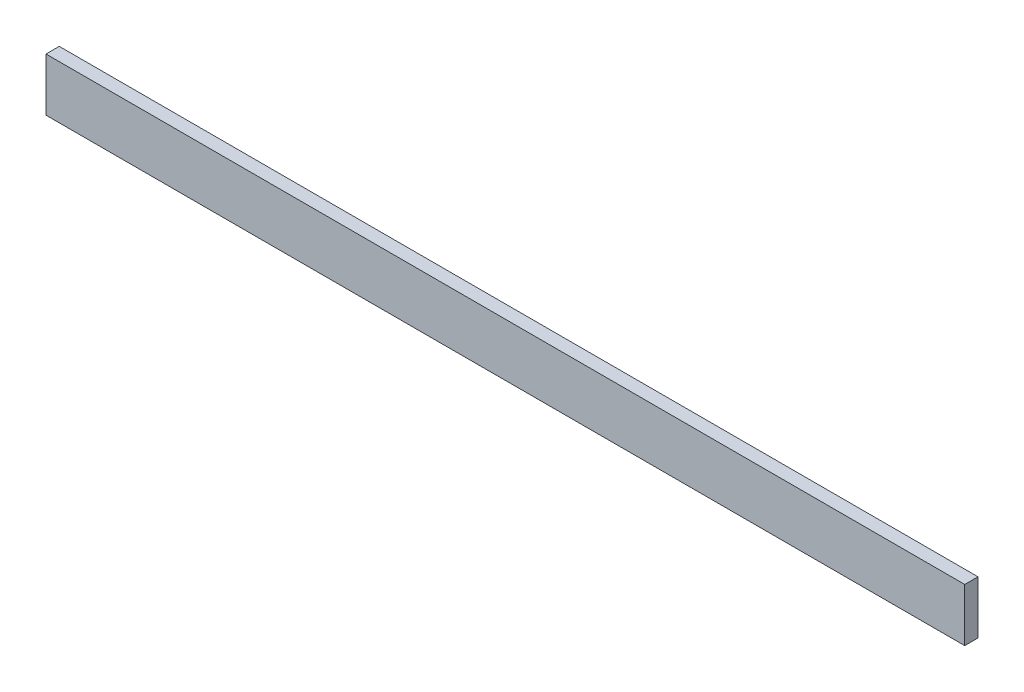
SolidWorks part; units mm, degrees
ref_plane "Alzado" through (0, 0, 0) normal (0, 0, 1) x (1, 0, 0)
ref_plane "Planta" through (0, 0, 0) normal (0, 1, 0) x (1, 0, 0)
ref_plane "Vista lateral" through (0, 0, 0) normal (1, 0, 0) x (0, 0, -1)
sketch "Croquis1" plane through (0, 0, 0) normal (0, 0, 1) x (1, 0, 0)
  line L1 (-59.767, 4.5111) -> (148.233, 4.5111)
  line L2 (-59.767, 4.5111) -> (-59.767, -7.4889)
  line L3 (-59.767, -7.4889) -> (148.233, -7.4889)
  line L4 (148.233, 4.5111) -> (148.233, -7.4889)
extrude "Saliente-Extruir1" add sketch "Croquis1" along normal blind 3
